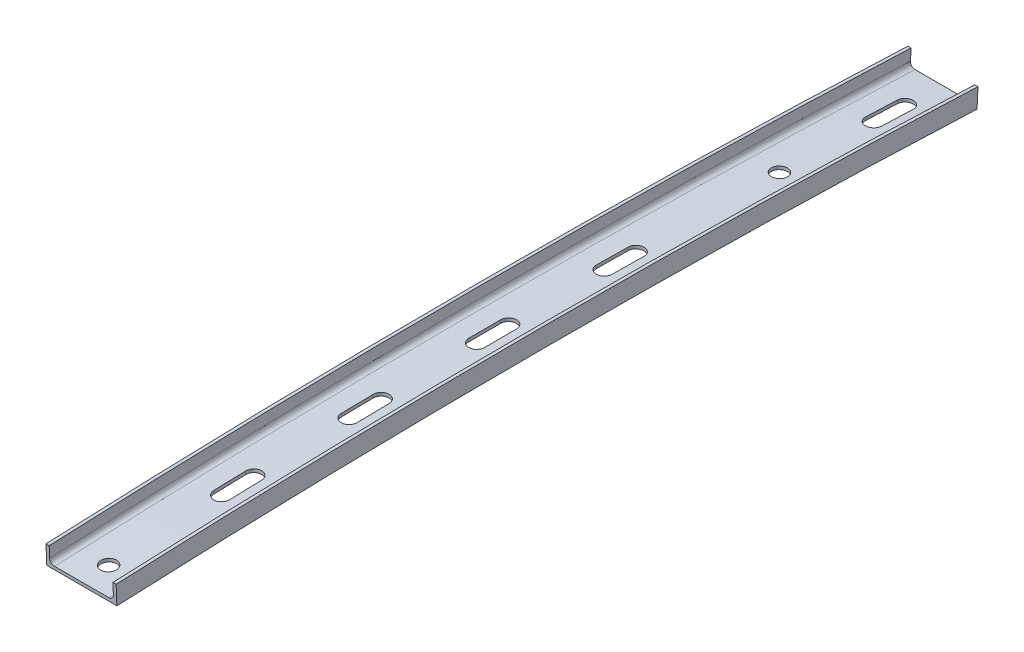
SolidWorks part; units mm, degrees
ref_plane "Front Plane" through (0, 0, 0) normal (0, 0, 1) x (1, 0, 0)
ref_plane "Top Plane" through (0, 0, 0) normal (0, 1, 0) x (1, 0, 0)
ref_plane "Right Plane" through (0, 0, 0) normal (1, 0, 0) x (0, 0, -1)
sketch "Sketch1" plane through (0, 0, 0) normal (0, 0, 1) x (1, 0, 0)
  line L0 (-17, 0) -> (17, 0)
  line L1 (-20, 3) -> (-20, 10)
  line L2 (-20, 10) -> (-22, 10)
  line L3 (-22, 10) -> (-22, -2)
  line L4 (-22, -2) -> (22, -2)
  line L5 (22, -2) -> (22, 10)
  line L6 (22, 10) -> (20, 10)
  line L7 (20, 10) -> (20, 3)
  arc A0 (17, 0) -> (20, 3) centre (17, 3) ccw
  arc A1 (-17, 0) -> (-20, 3) centre (-17, 3) cw
  point P4 (0, 0)
  point P12 (20, 0)
  point P15 (-20, 0)
  dimension "D4" = 3
  dimension "D1" = 2
  dimension "D2" = 2
  dimension "D3" = 40
  dimension "D5" = 10
sketch "Sketch3" plane through (0, 0, 0) normal (1, 0, 0) x (0, 0, -1)
  line L0 (-240, -6) -> (300, -6) construction
  arc A0 (-240, -6) -> (300, -6) centre (30, -6003) cw
  dimension "D1" = 540
  dimension "D2" = 6
  dimension "D3" = 300
sweep "Sweep1" add profiles "Sketch1" path "Sketch3"
sketch "Sketch4" plane through (0, 0, 0) normal (0, 1, 0) x (1, 0, 0)
  line L0 (0, 256.9001) -> (0, 276.9001) construction
  line L1 (-5, 256.9001) -> (-5, 276.9001)
  line L2 (5, 256.9001) -> (5, 276.9001)
  line L3 (0, 87.9001) -> (0, 107.9001) construction
  line L4 (-5, 87.9001) -> (-5, 107.9001)
  line L5 (5, 87.9001) -> (5, 107.9001)
  line L6 (0, -72.0999) -> (0, -52.0999) construction
  line L9 (0, 7.9001) -> (0, 27.9001) construction
  line L10 (-5, 7.9001) -> (-5, 27.9001)
  line L11 (5, 7.9001) -> (5, 27.9001)
  line L12 (-5, -72.0999) -> (-5, -52.0999)
  line L13 (5, -72.0999) -> (5, -52.0999)
  line L14 (-22, 299.9001) -> (22, 299.9001) construction
  line L15 (0, -152.0999) -> (0, -132.0999) construction
  line L16 (-5, -152.0999) -> (-5, -132.0999)
  line L17 (5, -152.0999) -> (5, -132.0999)
  arc A0 (-5, 256.9001) -> (5, 256.9001) centre (0, 256.9001) ccw
  arc A1 (5, 276.9001) -> (-5, 276.9001) centre (0, 276.9001) ccw
  arc A2 (-5, 87.9001) -> (5, 87.9001) centre (0, 87.9001) ccw
  arc A3 (5, 107.9001) -> (-5, 107.9001) centre (0, 107.9001) ccw
  arc A6 (-5, 7.9001) -> (5, 7.9001) centre (0, 7.9001) ccw
  arc A7 (5, 27.9001) -> (-5, 27.9001) centre (0, 27.9001) ccw
  arc A8 (-5, -72.0999) -> (5, -72.0999) centre (0, -72.0999) ccw
  arc A9 (5, -52.0999) -> (-5, -52.0999) centre (0, -52.0999) ccw
  arc A10 (-5, -152.0999) -> (5, -152.0999) centre (0, -152.0999) ccw
  arc A11 (5, -132.0999) -> (-5, -132.0999) centre (0, -132.0999) ccw
  circle A12 centre (0, 197.9001) radius 5
  circle A13 centre (0, -223.0999) radius 5
  point P3 (0, 266.9001)
  point P10 (0, 97.9001)
  point P17 (0, -62.0999)
  point P24 (0, 17.9001)
  point P33 (0, -142.0999)
  point P38 (0, 0)
  dimension "D1" = 5
  dimension "D3" = 33
  dimension "D9" = 10
  dimension "D10" = 10
  dimension "D2" = 20
  dimension "D4" = 202
  dimension "D5" = 282
  dimension "D6" = 362
  dimension "D7" = 442
  dimension "D8" = 102
  dimension "D11" = 523
extrude "Various mounting points" cut sketch "Sketch4" against normal through all both and the other way through all
